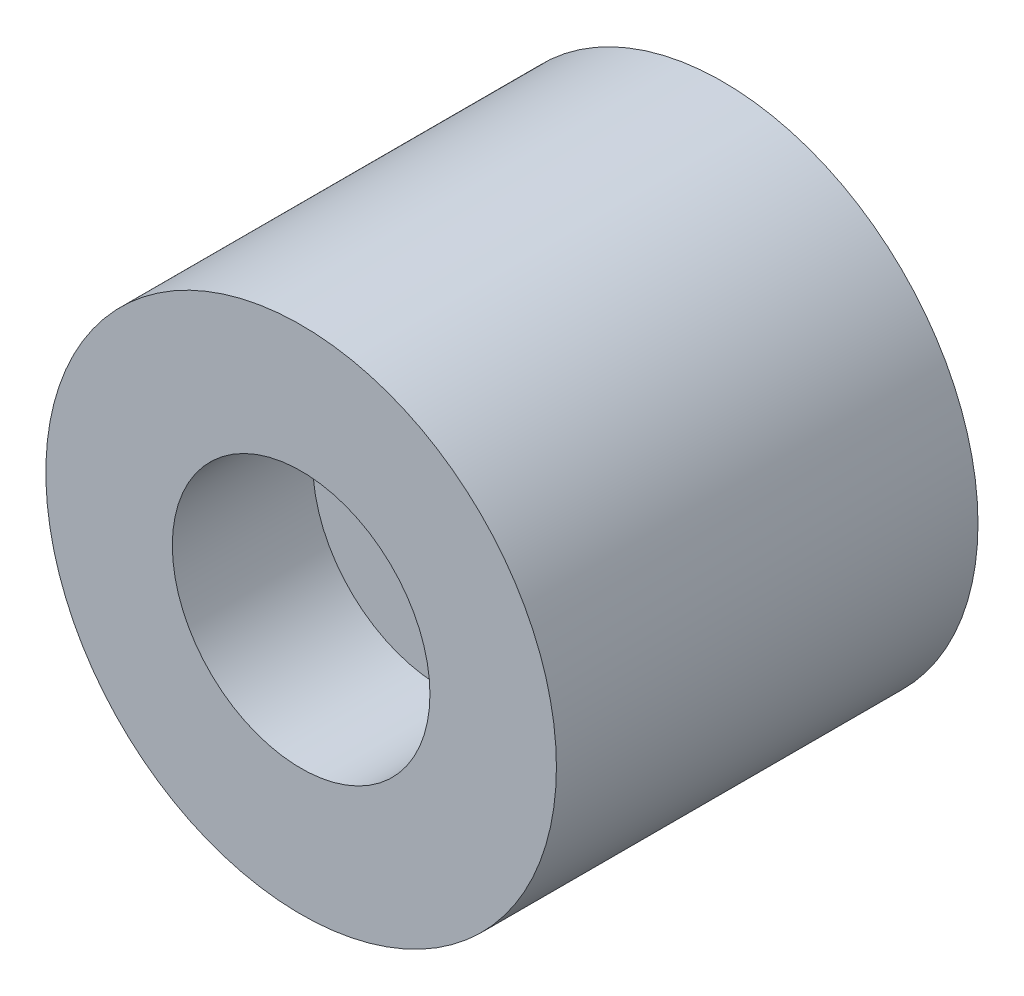
SolidWorks part; units mm, degrees
ref_plane "Front Plane" through (0, 0, 0) normal (0, 0, 1) x (1, 0, 0)
ref_plane "Top Plane" through (0, 0, 0) normal (0, 1, 0) x (1, 0, 0)
ref_plane "Right Plane" through (0, 0, 0) normal (1, 0, 0) x (0, 0, -1)
sketch "Sketch1" plane through (0, 0, 0) normal (0, 0, 1) x (1, 0, 0)
  circle A0 centre (0, 0) radius 5.45
  dimension "D1" = 10.9
extrude "Boss-Extrude1" add sketch "Sketch1" along normal blind 9 contours A0
sketch "Sketch2" plane through (0, 0, 9) normal (0, 0, 1) x (1, 0, 0)
  circle A0 centre (0, 0) radius 2.75
  dimension "D1" = 5.5
extrude "Cut-Extrude1" cut sketch "Sketch2" against normal blind 3
sketch "Sketch3" plane through (0, 0, 9) normal (0, 0, 1) x (1, 0, 0)
  circle A0 centre (0, 0) radius 5.45
  dimension "D1" = 10.9
